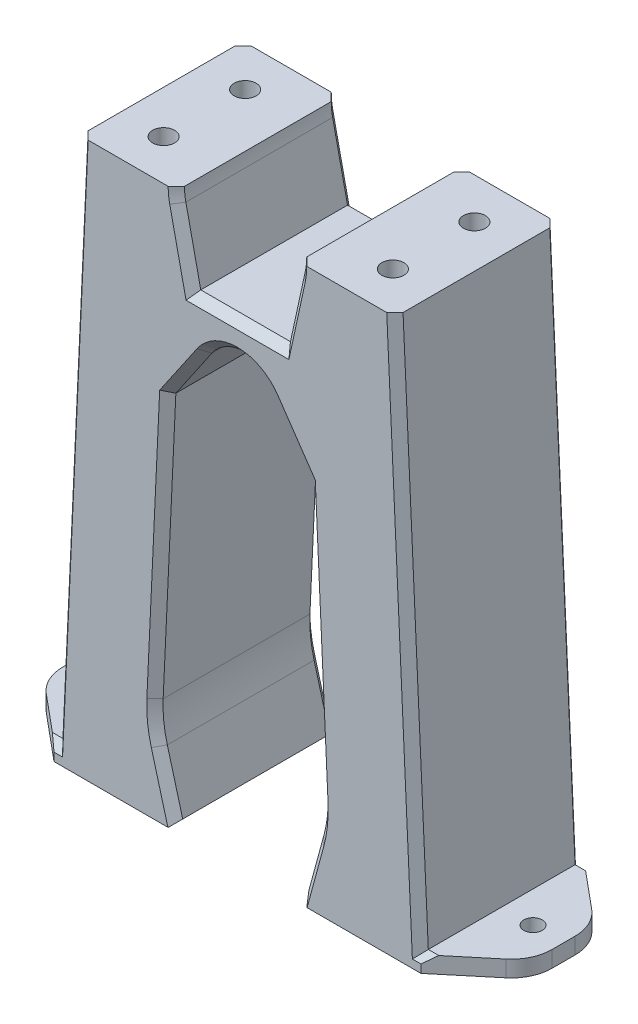
SolidWorks part; units mm, degrees
material "ABS"
ref_plane "Piano frontale" through (0, 0, 0) normal (0, 0, 1) x (1, 0, 0)
ref_plane "Piano superiore" through (0, 0, 0) normal (0, 1, 0) x (1, 0, 0)
ref_plane "Piano destro" through (0, 0, 0) normal (1, 0, 0) x (0, 0, -1)
sketch "Schizzo1" plane through (0, 0, 0) normal (0, 0, 1) x (1, 0, 0)
  line L0 (-14.6572, -3.1885) -> (-11, -20)
  line L1 (-11, -20) -> (11, -20)
  line L2 (11, -20) -> (14.6572, -3.1885)
  line L3 (-14.6572, -3.1885) -> (14.6572, -3.1885) construction
  line L4 (0, -20) -> (0, 0) construction
  line L5 (-15, 0) -> (15, 0) construction
  line L8 (-15, 0) -> (-38.6155, 0) construction
  line L9 (-38.6155, 0) -> (-35.6155, 4) construction
  line L10 (-35.6155, 4) -> (-20.6155, 4) construction
  line L11 (15, 0) -> (38.6155, 0) construction
  line L12 (38.6155, 0) -> (35.6155, 4) construction
  line L13 (35.6155, 4) -> (20.6155, 4) construction
  line L14 (-15, 0) -> (-38.6155, 0)
  line L15 (-38.6155, 0) -> (-44.8125, -132.2)
  line L17 (44.8125, -132.2) -> (38.6155, 0)
  line L18 (38.6155, 0) -> (15, 0)
  line L19 (0, -20) -> (0, -136.2) construction
  line L20 (-17.1094, -45) -> (-20.447, -116.2)
  line L21 (-20.447, -116.2) -> (-15, -136.2)
  line L22 (17.1094, -45) -> (20.447, -116.2)
  line L23 (20.447, -116.2) -> (15, -136.2)
  line L24 (-20.447, -116.2) -> (20.447, -116.2) construction
  line L25 (20.447, -116.2) -> (21.3845, -136.2) construction
  line L26 (-20.447, -116.2) -> (-21.3845, -136.2) construction
  line L27 (-45, -136.2) -> (-15, -136.2)
  line L28 (-15, -136.2) -> (15, -136.2)
  line L29 (15, -136.2) -> (45, -136.2)
  line L30 (-8.2524, -32.0583) -> (-17.1094, -45)
  line L31 (8.2524, -32.0583) -> (17.1094, -45)
  line L32 (-17.1094, -45) -> (-15, 0) construction
  line L33 (15, 0) -> (17.1094, -45) construction
  line L34 (-45, -136.2) -> (-45, -132.2)
  line L35 (-45, -132.2) -> (-44.8125, -132.2)
  line L36 (-44.8125, -132.2) -> (-45, -136.2) construction
  line L37 (45, -136.2) -> (45, -132.2)
  line L38 (45, -132.2) -> (44.8125, -132.2)
  line L39 (44.8125, -132.2) -> (45, -136.2) construction
  arc A0 (15, 0) -> (-15, 0) centre (0, 0) ccw construction
  arc A1 (20.6155, 4) -> (-20.6155, 4) centre (0, 0) ccw construction
  arc A2 (15, 0) -> (-15, 0) centre (0, 0) ccw construction
  arc A3 (-14.6572, -3.1885) -> (-15, 0) centre (0, 0) cw
  arc A4 (14.6572, -3.1885) -> (15, 0) centre (0, 0) ccw
  arc A5 (8.2524, -32.0583) -> (-8.2524, -32.0583) centre (0, -37.7061) ccw
  point P8 (0, -3.1885)
  point P24 (0, -116.2)
  point P31 (0, -136.2)
  dimension "D2" = 15
  dimension "D4" = 6
  dimension "D13" = 10
  dimension "D1" = 22
  dimension "D3" = 20
  dimension "D5" = 4
  dimension "D6" = 15
  dimension "D7" = 3
  dimension "D8" = 90
  dimension "D9" = 116.2
  dimension "D10" = 20
  dimension "D11" = 30
  dimension "D12" = 25
  dimension "D14" = 4
  dimension "D15" = 4
extrude "Estrusione-Estrusione1" add sketch "Schizzo1" along normal blind 40 contours L0 A3 L14 L15 L27 L21 L20 L30 L1 | A4 L2 L1 L31 L22 L23 L29 L17 L18
hole_wizard "Foro per Vite M4-1" positions "Schizzo4" profile "Schizzo5" hole size "M4" standard "DIN"
sketch "Schizzo4" plane through (0, 0, 0) normal (0, 1, 0) x (1, 0, 0)
  line L0 (-28.1155, -30) -> (-28.1155, -10) construction
  line L1 (-28.1155, -10) -> (28.1155, -10) construction
  line L2 (28.1155, -10) -> (28.1155, -30) construction
  line L3 (28.1155, -30) -> (-28.1155, -30) construction
  line L4 (-28.1155, -30) -> (-28.1155, -20) construction
  line L5 (-28.1155, -20) -> (-38.6155, -20) construction
  line L6 (-38.6155, -40) -> (-38.6155, 0) construction
  line L14 (38.6155, -40) -> (38.6155, 0) construction
  point P0 (-28.1155, -10)
  point P2 (-28.1155, -30)
  point P4 (28.1155, -30)
  point P6 (28.1155, -10)
  dimension "D1" = 20
  dimension "D2" = 10.5
  dimension "D3" = 10.5
sketch "Schizzo5" plane through (-28.1155, 0, 10) normal (1, 0, 0) x (0, 0, 1)
  line L0 (0, 0) -> (0, 16.6223)
  line L1 (0, 16.6223) -> (2.7, 15)
  line L2 (2.7, 15) -> (2.7, 0)
  line L5 (2.7, 0) -> (0, 0)
  line L10 (0, 16.6223) -> (-2.7, 15) construction
  line L11 (0, -6.35) -> (0, 107.95) construction
  dimension "Hole Dia." = 5.4
  dimension "Hole Depth" = 15
  dimension "Drill Angle" = 118
sketch "Schizzo6" plane through (0, -136.2, 0) normal (0, -1, 0) x (1, 0, 0)
  line L0 (-45, 40) -> (-60, 27.5)
  line L1 (-60, 27.5) -> (-60, 12.5)
  line L2 (-60, 12.5) -> (-45, 0)
  line L3 (-45, 0) -> (-45, 40)
  line L4 (45, 40) -> (60, 27.5)
  line L5 (60, 27.5) -> (60, 12.5)
  line L6 (60, 12.5) -> (45, 0)
  line L7 (45, 0) -> (45, 40)
  line L8 (-60, 20) -> (60, 20) construction
  line L9 (0, 0) -> (0, 20) construction
  line L10 (15, 0) -> (45, 0) construction
  dimension "D1" = 15
  dimension "D2" = 15
extrude "Estrusione-Estrusione2" add sketch "Schizzo6" against normal blind 4
sketch "Schizzo7" plane through (0, -132.2, 0) normal (0, 1, 0) x (1, 0, 0)
  line L0 (-60, -20) -> (60, -20) construction
  line L1 (-60, -27.5) -> (-60, -12.5) construction
  line L2 (60, -12.5) -> (60, -27.5) construction
  point P0 (-52.5, -20)
  point P2 (52.5, -20)
  dimension "D1" = 7.5
  dimension "D2" = 7.5
hole_wizard "Foro per Vite M4-2" positions "Schizzo7" profile "Schizzo8" hole size "M4" standard "DIN"
sketch "Schizzo8" plane through (-52.5, -132.2, 20) normal (1, 0, 0) x (0, 0, 1)
  line L0 (0, 0) -> (0, 81.3519)
  line L1 (0, 81.3519) -> (2.25, 80)
  line L2 (2.25, 80) -> (2.25, 0)
  line L5 (2.25, 0) -> (0, 0)
  line L10 (0, 81.3519) -> (-2.25, 80) construction
  line L11 (0, -6.35) -> (0, 107.95) construction
  dimension "Hole Dia." = 4.5
  dimension "Hole Depth" = 80
  dimension "Drill Angle" = 118
fillet "Raccordo1" radius 10 4 edges at (60, -134.2, 12.5) (60, -134.2, 27.5) (-60, -134.2, 12.5) (-60, -134.2, 27.5)
fillet "Raccordo2" radius 30 2 edges at (20.447, -116.2, 20) (-20.447, -116.2, 20)
chamfer "Smusso1" distance 2 angle 45 41 edges at (38.6155, 0, 20) (14.9141, -1.6035, 40) (-14.9141, -1.6035, 40) (12.8286, -11.5943, 40) (0, -20, 40) (-12.8286, -11.5943, 40) (-38.6155, 0, 20) (-14.9141, -1.6035, 0) (14.9141, -1.6035, 0) (-12.8286, -11.5943, 0) (12.8286, -11.5943, 0) (0, -20, 0) (-26.8078, 0, 0) (-41.714, -66.1, 0) (-44.9062, -132.2, 0) (-18.6674, -78.2377, 0) (-20.0786, -116.1595, 0) (-17.102, -128.4817, 0) (-15, -136.2, 20) (15, -136.2, 20) (18.6674, -78.2377, 0) (20.0786, -116.1595, 0) (17.102, -128.4817, 0) (26.8078, 0, 0) (41.714, -66.1, 0) (44.9062, -132.2, 0) (26.8078, 0, 40) (44.9062, -132.2, 40) (41.714, -66.1, 40) (17.102, -128.4817, 40) (20.0786, -116.1595, 40) (18.6674, -78.2377, 40) (12.6809, -38.5292, 40) (0, -27.7061, 40) (-12.6809, -38.5292, 40) (-18.6674, -78.2377, 40) (-20.0786, -116.1595, 40) (-17.102, -128.4817, 40) (-26.8078, 0, 40) (-44.9062, -132.2, 40) (-41.714, -66.1, 40)
